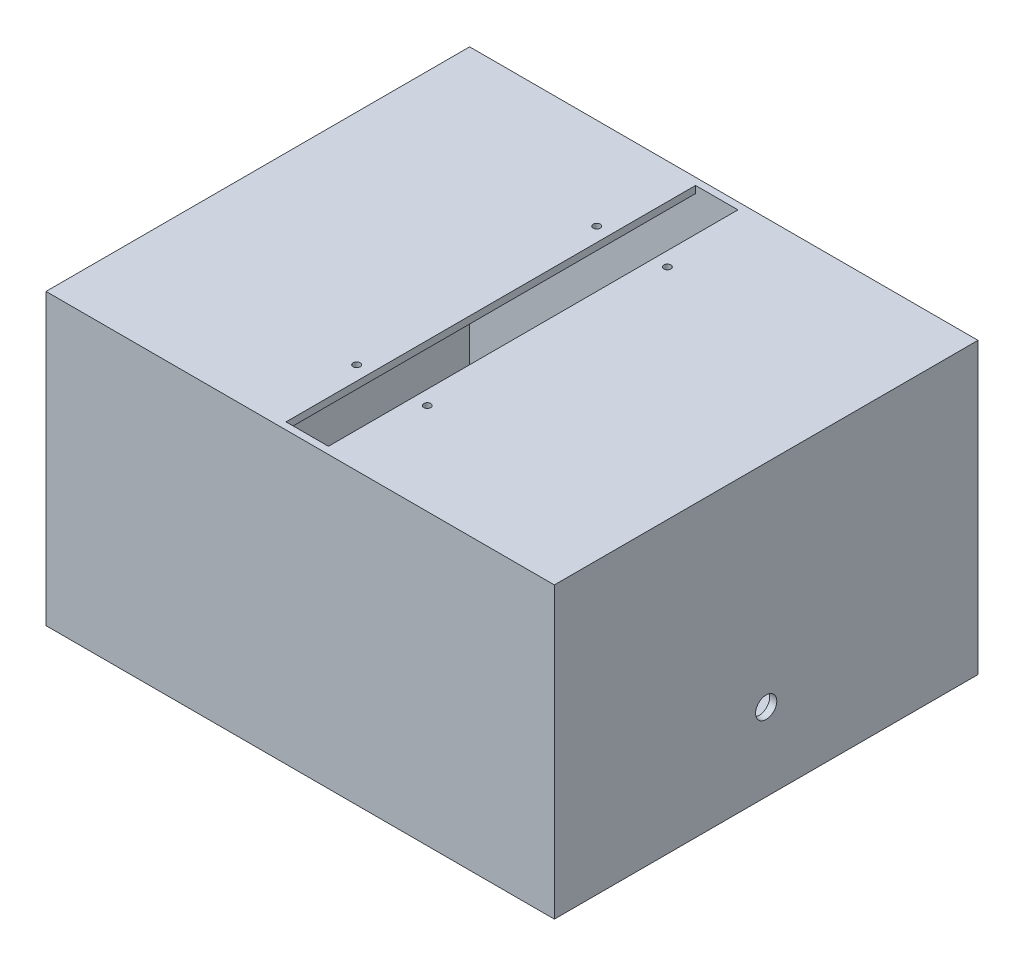
SolidWorks part; units mm, degrees
ref_plane "Front Plane" through (0, 0, 0) normal (0, 0, 1) x (1, 0, 0)
ref_plane "Top Plane" through (0, 0, 0) normal (0, 1, 0) x (1, 0, 0)
ref_plane "Right Plane" through (0, 0, 0) normal (1, 0, 0) x (0, 0, -1)
sketch "Sketch1" plane through (0, 0, 0) normal (0, 1, 0) x (1, 0, 0)
  line L0 (250, 0) -> (0, 0) construction
  line L1 (0, 0) -> (-250, 0) construction
  line L2 (-180, -150) -> (180, -150)
  line L3 (-180, -150) -> (-180, 150)
  line L4 (180, -150) -> (180, 150)
  line L5 (-180, 150) -> (180, 150)
  line L6 (-180, -150) -> (180, 150) construction
  line L7 (180, -150) -> (-180, 150) construction
  dimension "D1" = 300
  dimension "D2" = 360
extrude "Boss-Extrude1" add sketch "Sketch1" against normal blind 200
sketch "Sketch2" plane through (0, -200, 0) normal (0, -1, 0) x (1, 0, 0)
  line L0 (-180, 150) -> (180, 150) construction
  line L1 (-175, -145) -> (175, -145)
  line L2 (-175, -145) -> (-175, 145)
  line L3 (-175, 145) -> (175, 145)
  line L4 (175, -145) -> (175, 145)
  line L5 (-175, -145) -> (175, 145) construction
  line L6 (-175, 145) -> (175, -145) construction
  line L7 (180, 150) -> (180, -150) construction
  point P0 (0, 0)
  dimension "D1" = 5
  dimension "D2" = 5
extrude "Cut-Extrude1" cut sketch "Sketch2" against normal blind 195
sketch "Sketch3" plane through (0, 0, 0) normal (0, 1, 0) x (1, 0, 0)
  line L0 (-180, 0) -> (180, 0) construction
  line L1 (-180, 150) -> (-180, -150) construction
  line L2 (180, -150) -> (180, 150) construction
  line L3 (0, 150) -> (0, -120.2082) construction
  line L4 (-15, -145) -> (15, -145)
  line L5 (-15, -145) -> (-15, 145)
  line L6 (-15, 145) -> (15, 145)
  line L7 (15, -145) -> (15, 145)
  line L8 (-15, -145) -> (15, 145) construction
  line L9 (-15, 145) -> (15, -145) construction
  line L10 (180, 150) -> (-180, 150) construction
  point P6 (0, 0)
  dimension "D1" = 30
  dimension "D2" = 5
extrude "Cut-Extrude2" cut sketch "Sketch3" against normal through all
sketch "Sketch4" plane through (-180, 0, 0) normal (-1, 0, 0) x (0, 0, 1)
  line L0 (0, 0) -> (0, -200) construction
  line L1 (-150, -200) -> (150, -200) construction
  circle A0 centre (0, -150) radius 7.5
  point P7 (0, -100)
  point P8 (0, -100)
  point P10 (0, -150)
  dimension "D1" = 50
  dimension "D2" = 15
extrude "Cut-Extrude3" cut sketch "Sketch4" against normal through all
sketch "Sketch5" plane through (0, 0, 0) normal (0, 1, 0) x (1, 0, 0)
  line L0 (0, 150) -> (0, -150) construction
  line L1 (180, 150) -> (-180, 150) construction
  line L2 (-180, -150) -> (180, -150) construction
  line L3 (25, 150) -> (25, -150) construction
  line L4 (-25, 150) -> (-25, -150) construction
  line L5 (-180, 0) -> (180, 0) construction
  line L6 (-180, 150) -> (-180, -150) construction
  line L7 (180, -150) -> (180, 150) construction
  circle A0 centre (-25, 85) radius 2.5
  circle A1 centre (25, 85) radius 2.5
  circle A2 centre (25, -85) radius 2.5
  circle A3 centre (-25, -85) radius 2.5
  dimension "D4" = 5
  dimension "D1" = 25
  dimension "D2" = 25
  dimension "D3" = 85
extrude "Cut-Extrude4" cut sketch "Sketch5" against normal up to surface (5 mm away) up to face at (-95, -5, 0)
sketch "Sketch6" plane through (0, -200, 0) normal (0, -1, 0) x (1, 0, 0)
  line L1 (-180, 150) -> (180, 150)
  line L2 (-180, 150) -> (-180, -150)
  line L3 (-180, -150) -> (180, -150)
  line L4 (180, 150) -> (180, -150)
extrude "Boss-Extrude2" add sketch "Sketch6" along normal blind 5
sketch "Sketch7" plane through (0, 0, -150) normal (0, 0, -1) x (-1, 0, 0)
  line L0 (0, 0) -> (0, -205) construction
  line L1 (180, -205) -> (-180, -205) construction
  line L2 (-180, -200) -> (180, -200) construction
  line L3 (-180, -205) -> (-180, 0) construction
  line L4 (180, -205) -> (180, 0) construction
  line L6 (-100, -200) -> (100, -200)
  line L7 (-100, -200) -> (-100, -173)
  line L8 (-100, -173) -> (100, -173)
  line L9 (100, -200) -> (100, -173)
  line L10 (-100, -200) -> (100, -173) construction
  line L11 (-100, -173) -> (100, -200) construction
  point P11 (0, -186.5)
  dimension "D1" = 5
  dimension "D2" = 200
  dimension "D3" = 27
extrude "Cut-Extrude5" cut sketch "Sketch7" against normal up to surface (5 mm away) up to face at (0, -52.5, -145)
